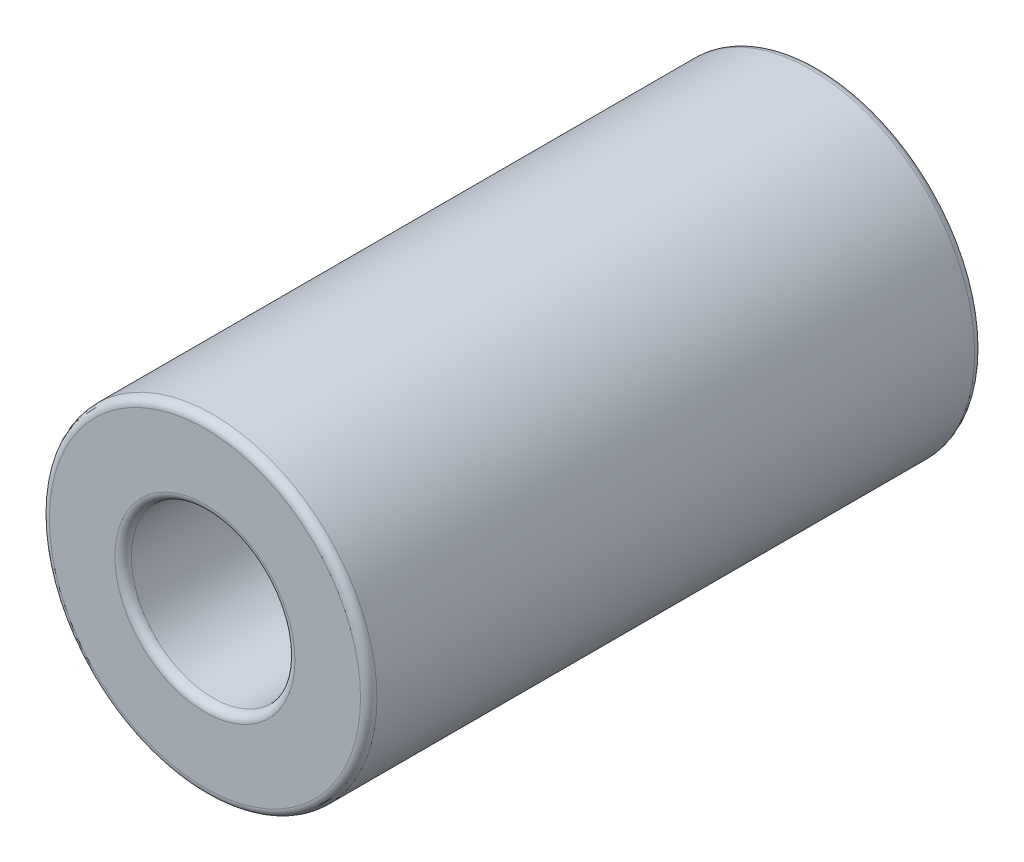
SolidWorks part; units mm, degrees
ref_plane "前视基准面" through (0, 0, 0) normal (0, 0, 1) x (1, 0, 0)
ref_plane "上视基准面" through (0, 0, 0) normal (0, 1, 0) x (1, 0, 0)
ref_plane "右视基准面" through (0, 0, 0) normal (1, 0, 0) x (0, 0, -1)
sketch "草图1" plane through (0, 0, 0) normal (0, 0, 1) x (1, 0, 0)
  circle A0 centre (0, 0) radius 2
  circle A1 centre (0, 0) radius 4
extrude "凸台-拉伸1" add sketch "草图1" against normal blind 15
fillet "圆角1" radius 0.2 4 edges at (4, 0, -15) (2, 0, -15) (4, 0, 0) (2, 0, 0)
